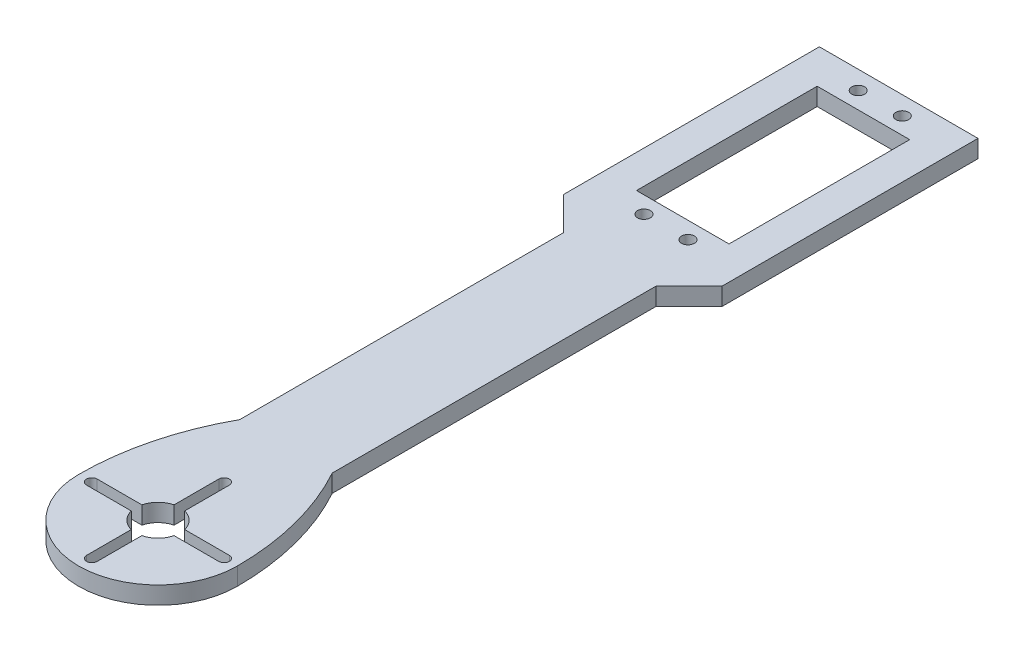
SolidWorks part; units mm, degrees
ref_plane "정면" through (0, 0, 0) normal (0, 0, 1) x (1, 0, 0)
ref_plane "윗면" through (0, 0, 0) normal (0, 1, 0) x (1, 0, 0)
ref_plane "우측면" through (0, 0, 0) normal (1, 0, 0) x (0, 0, -1)
sketch "스케치1" plane through (0, 0, 0) normal (0, 1, 0) x (1, 0, 0)
  line L0 (0, 0) -> (0, 150) construction
  line L1 (-15, 0) -> (15, 0) construction
  line L2 (-5, 115.28) -> (5, 115.28) construction
  line L3 (-5, 115.28) -> (-5, 163.91) construction
  line L4 (-5, 163.91) -> (5, 163.91) construction
  line L5 (5, 115.28) -> (5, 163.91) construction
  line L6 (-5, 115.28) -> (5, 163.91) construction
  line L7 (-5, 163.91) -> (5, 115.28) construction
  line L8 (-10.5, 160.095) -> (10.5, 160.095)
  line L9 (-10.5, 160.095) -> (-10.5, 119.095)
  line L10 (-10.5, 119.095) -> (10.5, 119.095)
  line L11 (10.5, 160.095) -> (10.5, 119.095)
  line L12 (-10.5, 160.095) -> (10.5, 119.095) construction
  line L13 (-10.5, 119.095) -> (10.5, 160.095) construction
  line L14 (-15, 1.2) -> (15, 1.2)
  line L15 (-15, -1.2) -> (15, -1.2)
  line L16 (0, 15) -> (0, -15) construction
  line L17 (1.2, 15) -> (1.2, -15)
  line L18 (-1.2, 15) -> (-1.2, -15)
  line L19 (18, 168.095) -> (-18, 168.095)
  line L20 (-18, 168.095) -> (-18, 0)
  line L21 (18, 0) -> (18, 168.095)
  circle A0 centre (-5, 163.91) radius 1.45
  circle A1 centre (5, 163.91) radius 1.45
  circle A2 centre (-5, 115.28) radius 1.45
  circle A3 centre (5, 115.28) radius 1.45
  circle A4 centre (0, 0) radius 5
  arc A5 (-15, 1.2) -> (-15, -1.2) centre (-15, 0) ccw
  arc A6 (15, -1.2) -> (15, 1.2) centre (15, 0) ccw
  arc A7 (1.2, 15) -> (-1.2, 15) centre (0, 15) ccw
  arc A8 (-1.2, -15) -> (1.2, -15) centre (0, -15) ccw
  arc A9 (-18, 0) -> (18, 0) centre (0, 0) ccw
  point P3 (0, 139.595)
  point P12 (0, 139.595)
  point P20 (0, 0)
  point P26 (0, 0)
  dimension "D2" = 2.9
  dimension "D8" = 10
  dimension "D11" = 1.2
  dimension "D12" = 1.2
  dimension "D13" = 18
  dimension "D1" = 150
  dimension "D3" = 10
  dimension "D4" = 48.63
  dimension "D5" = 13.91
  dimension "D6" = 21
  dimension "D7" = 41
  dimension "D9" = 30
  dimension "D10" = 30
  dimension "D14" = 8
extrude "보스-돌출1" add sketch "스케치1" along normal blind 4 contours L20 A9 L21 L19 L8 L11 L10 L9 A0 A1 A2 A3 A8 L18 A4 L15 A5 L14 A7 L17 A6
sketch "스케치2" plane through (0, 4, 0) normal (0, 1, 0) x (1, 0, 0)
  line L0 (0, 0) -> (0, 148.8699) construction
  line L1 (-18, 110) -> (-10.5, 102.5)
  line L2 (-18, 168.095) -> (-18, 0) construction
  line L3 (-10.5, 102.5) -> (-10.5, 29.0474)
  line L4 (-18, 110) -> (-18, 0)
  arc A0 (-18, 0) -> (-10.5, 29.0474) centre (42, 0) cw
  point P10 (-10.5, 22.76)
  point P12 (-10.5, 14.1558)
  point P13 (-10.5, 9.1042)
  point P14 (-10.5, 31.4803)
  dimension "D1" = 21
  dimension "D4" = 60
  dimension "D2" = 45
  dimension "D3" = 110
extrude "컷-돌출1" cut sketch "스케치2" against normal through all
mirror "대칭 복사1" about plane through (0, 0, 0) normal (1, 0, 0) of "컷-돌출1"
sketch "스케치3" plane through (0, 0, 0) normal (1, 0, 0) x (0, 0, -1)
  line L1 (29.0474, 0) -> (102.5, 0) construction
  line L2 (25, 0) -> (105, 0)
  arc A0 (25, 0) -> (105, 0) centre (65, 144.5683) ccw
  dimension "D1" = 25
  dimension "D3" = 150
  dimension "D2" = 80
extrude "보스-돌출2" add sketch "스케치3" along normal mid plane 4
